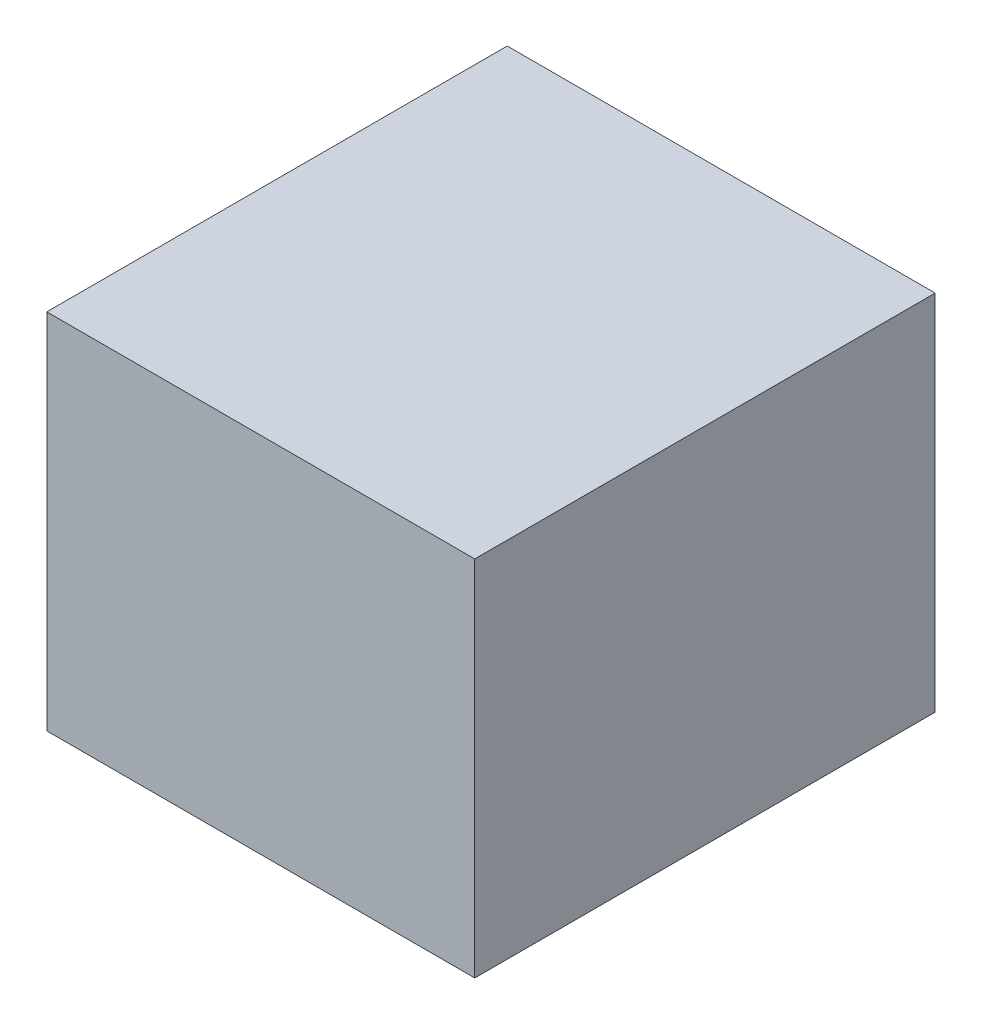
SolidWorks part; units mm, degrees
ref_plane "Ön Düzlem" through (0, 0, 0) normal (0, 0, 1) x (1, 0, 0)
ref_plane "Üst Düzlem" through (0, 0, 0) normal (0, 1, 0) x (1, 0, 0)
ref_plane "Sağ Düzlem" through (0, 0, 0) normal (1, 0, 0) x (0, 0, -1)
sketch "Çizim1" plane through (0, 0, 0) normal (0, 0, 1) x (1, 0, 0)
  line L1 (-71.2245, 41.7431) -> (7.7755, 41.7431)
  line L2 (-71.2245, 41.7431) -> (-71.2245, -25.2569)
  line L3 (-71.2245, -25.2569) -> (7.7755, -25.2569)
  line L4 (7.7755, 41.7431) -> (7.7755, -25.2569)
extrude "Yükseklik-Ekstrüzyon1" add sketch "Çizim1" along normal blind 85
